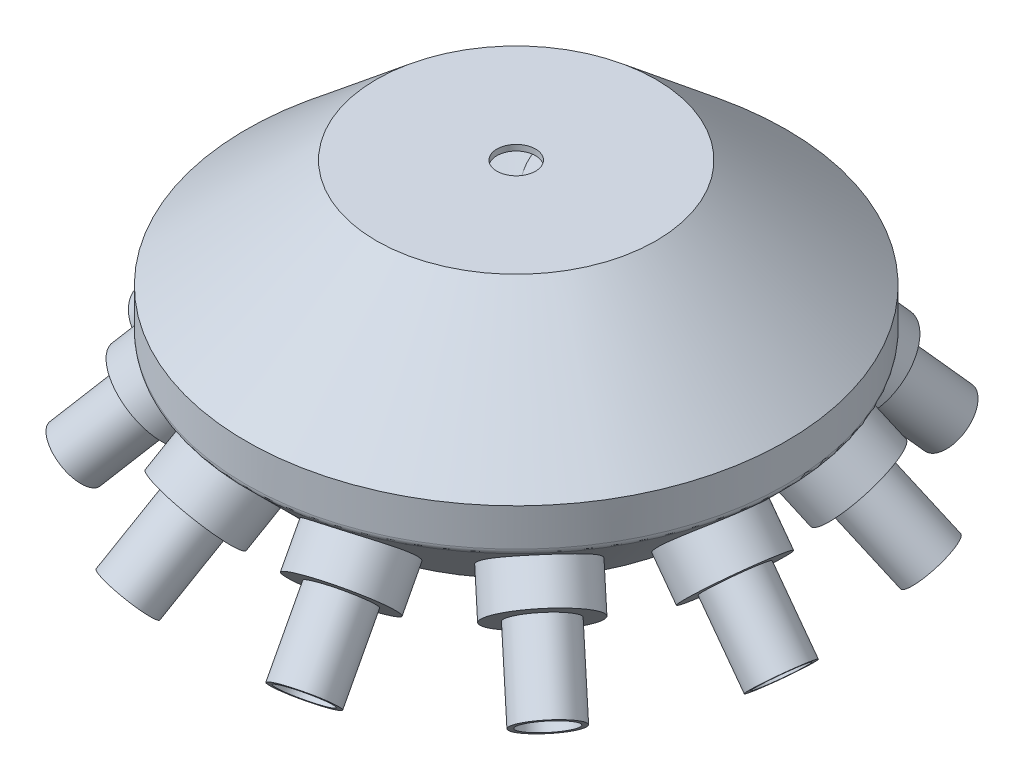
SolidWorks part; units mm, degrees
ref_plane "Front Plane" through (0, 0, 0) normal (0, 0, 1) x (1, 0, 0)
ref_plane "Top Plane" through (0, 0, 0) normal (0, 1, 0) x (1, 0, 0)
ref_plane "Right Plane" through (0, 0, 0) normal (1, 0, 0) x (0, 0, -1)
sketch "Sketch1" plane through (0, 0, 0) normal (0, 0, 1) x (1, 0, 0)
  line L2 (0, 147.6375) -> (0, 0)
  line L3 (128.4086, 0) -> (0, 0)
  line L4 (0, -40.1687) -> (0, 183.5289) construction
  line L5 (177.8, 76.2) -> (177.8, 49.3914)
  line L6 (177.8, 49.3914) -> (128.4086, 0)
  line L8 (177.8, 76.2) -> (92.075, 147.6375)
  line L9 (92.075, 147.6375) -> (0, 147.6375)
  point P0 (0, 183.5289)
  point P1 (0, 119.3081)
  dimension "D1" = 76.2
  dimension "D2" = 177.8
  dimension "D3" = 69.85
  dimension "D4" = 135
  dimension "D5" = 92.075
  dimension "D6" = 147.6375
revolve "Revolve1" add sketch "Sketch1" angle 360 about L4
shell "Shell1" thickness 3.81
fillet "Fillet2" radius 5.08 1 edges at (0, 49.3914, -177.8)
ref_plane "Plane1" through (0, -64.2043, -64.2043) normal (0, -0.7071, -0.7071) x (-1, 0, 0)
sketch "Sketch4" plane through (0, -64.2043, -64.2043) normal (0, -0.7071, -0.7071) x (-1, 0, 0)
  line L0 (0, 81.2006) -> (0, -81.2006) construction
  circle A0 centre (0, 124.2544) radius 30.1625
  ellipse E1 centre (0, 33.8729) end of major axis (-176.3121, 33.8729) minor radius 124.6715 construction
  point P10 (0, 158.5444)
  dimension "D2" = 60.325
  dimension "D1" = 34.29
extrude "Boss-Extrude1" add sketch "Sketch4" along normal blind 25.4 and the other way blind 6.35
sketch "Sketch5" plane through (0, -82.1648, -82.1648) normal (0, -0.7071, -0.7071) x (1, 0, 0)
  circle A0 centre (0, -124.2544) radius 30.1625 construction
  circle A1 centre (0, -124.2544) radius 30.1625 construction
  circle A2 centre (0, -124.2544) radius 15.875
  circle A3 centre (0, -124.2544) radius 19.05
  dimension "D1" = 31.75
  dimension "D2" = 38.1
extrude "Boss-Extrude2" add sketch "Sketch5" along normal blind 50.8
pattern_circular "CirPattern2" count 11 over 360 about axis through (0, 0, 0) along (0, 1, 0) of "Boss-Extrude1", "Boss-Extrude2"
sketch "Sketch6" plane through (0, 147.6375, 0) normal (0, 1, 0) x (1, 0, 0)
  circle A0 centre (0, 0) radius 12.7
  dimension "D1" = 25.4
extrude "Cut-Extrude1" cut sketch "Sketch6" against normal through all
